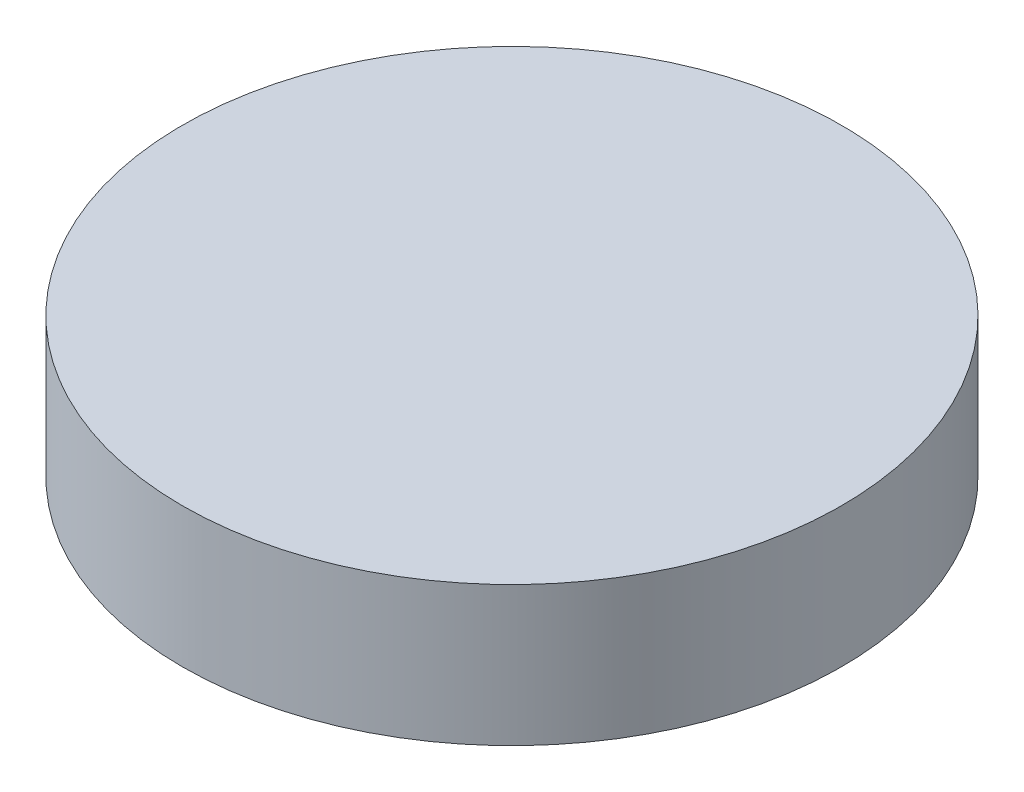
SolidWorks part; units mm, degrees
ref_plane "Plan de face" through (0, 0, 0) normal (0, 0, 1) x (1, 0, 0)
ref_plane "Plan de dessus" through (0, 0, 0) normal (0, 1, 0) x (1, 0, 0)
ref_plane "Plan de droite" through (0, 0, 0) normal (1, 0, 0) x (0, 0, -1)
sketch "Esquisse1" plane through (0, 0, 0) normal (0, 1, 0) x (1, 0, 0)
  circle A0 centre (0, 0) radius 15
  dimension "D1" = 30
extrude "Boss.-Extru.1" add sketch "Esquisse1" along normal blind 6.35
